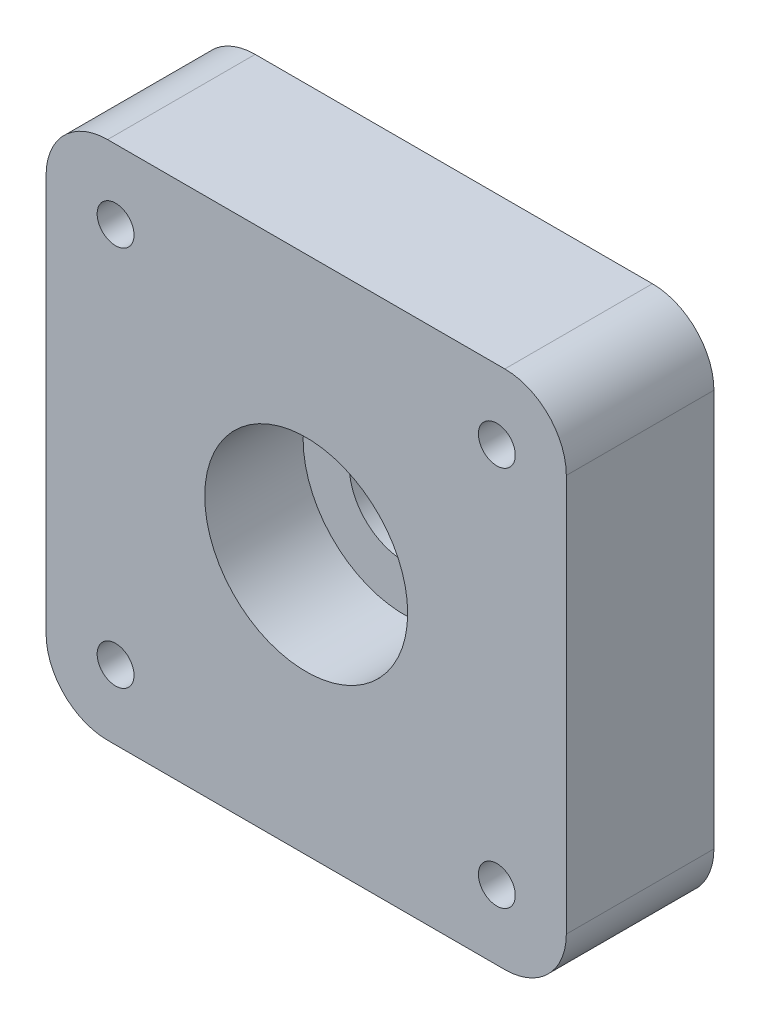
SolidWorks part; units mm, degrees
ref_plane "Alzado" through (0, 0, 0) normal (0, 0, 1) x (1, 0, 0)
ref_plane "Planta" through (0, 0, 0) normal (0, 1, 0) x (1, 0, 0)
ref_plane "Vista lateral" through (0, 0, 0) normal (1, 0, 0) x (0, 0, -1)
sketch "Croquis1" plane through (0, 0, 0) normal (0, 0, 1) x (1, 0, 0)
  line L0 (0, 25.4786) -> (0, -27.3465) construction
  line L1 (-21.15, -21.15) -> (21.15, -21.15)
  line L2 (-21.15, -21.15) -> (-21.15, 21.15)
  line L3 (-21.15, 21.15) -> (21.15, 21.15)
  line L4 (21.15, -21.15) -> (21.15, 21.15)
  line L5 (-21.15, -21.15) -> (21.15, 21.15) construction
  line L6 (-21.15, 21.15) -> (21.15, -21.15) construction
  line L7 (-15.5, 15.5) -> (-15.5, -15.5) construction
  line L8 (15.5, 15.5) -> (15.5, -15.5) construction
  circle A0 centre (-15.5, 15.5) radius 1.5
  circle A1 centre (-15.5, -15.5) radius 1.5
  circle A2 centre (15.5, -15.5) radius 1.5
  circle A3 centre (15.5, 15.5) radius 1.5
  point P0 (0, 0)
  dimension "D3" = 3
  dimension "D1" = 42.3
  dimension "D2" = 42.3
  dimension "D4" = 15.5
extrude "Saliente-Extruir1" add sketch "Croquis1" along normal mid plane 12
fillet "Redondeo1" radius 5 4 edges at (-21.15, 21.15, 0) (-21.15, -21.15, 0) (21.15, -21.15, 0) (21.15, 21.15, 0)
sketch "Croquis2" plane through (0, 0, 6) normal (0, 0, 1) x (1, 0, 0)
  circle A0 centre (0, 0) radius 8.25
  dimension "D1" = 16.5
extrude "Cortar-Extruir1" cut sketch "Croquis2" against normal blind 8
sketch "Croquis3" plane through (0, 0, -6) normal (0, 0, -1) x (-1, 0, 0)
  circle A0 centre (0, 0) radius 4.5
  dimension "D1" = 9
extrude "Cortar-Extruir2" cut sketch "Croquis3" against normal blind 10
